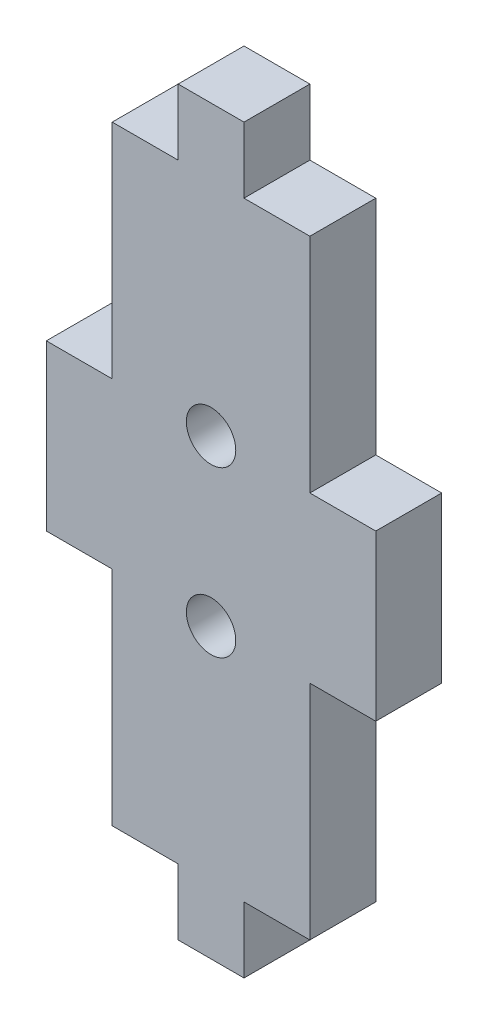
SolidWorks part; units mm, degrees
ref_plane "Спереди" through (0, 0, 0) normal (0, 0, 1) x (1, 0, 0)
ref_plane "Сверху" through (0, 0, 0) normal (0, 1, 0) x (1, 0, 0)
ref_plane "Справа" through (0, 0, 0) normal (1, 0, 0) x (0, 0, -1)
other "Configuration Table"
sketch "Эскиз1" plane through (0, 0, 0) normal (0, 0, 1) x (1, 0, 0)
  line L0 (0, 18.5) -> (7, 18.5) construction
  line L1 (0, 0) -> (4, 0)
  line L2 (0, 0) -> (0, 13.5)
  line L3 (0, 37) -> (4, 37)
  line L4 (12, 0) -> (12, 13.5)
  line L5 (6, 52) -> (6, 0) construction
  line L6 (0, 23.5) -> (-4, 23.5)
  line L7 (-4, 23.5) -> (-4, 13.5)
  line L8 (0, 13.5) -> (-4, 13.5)
  line L9 (12, 13.5) -> (16, 13.5)
  line L10 (16, 23.5) -> (16, 13.5)
  line L11 (12, 23.5) -> (16, 23.5)
  line L12 (12, 23.5) -> (12, 37)
  line L13 (0, 23.5) -> (0, 37)
  line L14 (4, 37) -> (4, 41)
  line L15 (4, 41) -> (8, 41)
  line L16 (8, 37) -> (8, 41)
  line L17 (8, 37) -> (12, 37)
  line L18 (8, 0) -> (8, -4)
  line L19 (4, -4) -> (8, -4)
  line L20 (4, 0) -> (4, -4)
  line L21 (8, 0) -> (12, 0)
  circle A0 centre (6, 23.5) radius 1.5
  circle A1 centre (6, 13.5) radius 1.5
  point P13 (-4, 18.5)
  point P18 (6, -4)
  point P23 (6, 41)
  dimension "D7" = 3
  dimension "D1" = 12
  dimension "D2" = 4
  dimension "D3" = 10
  dimension "D4" = 37
  dimension "D5" = 4
  dimension "D6" = 4
  dimension "D8" = 10
extrude "Бобышка-Вытянуть1" add sketch "Эскиз1" along normal blind 4
